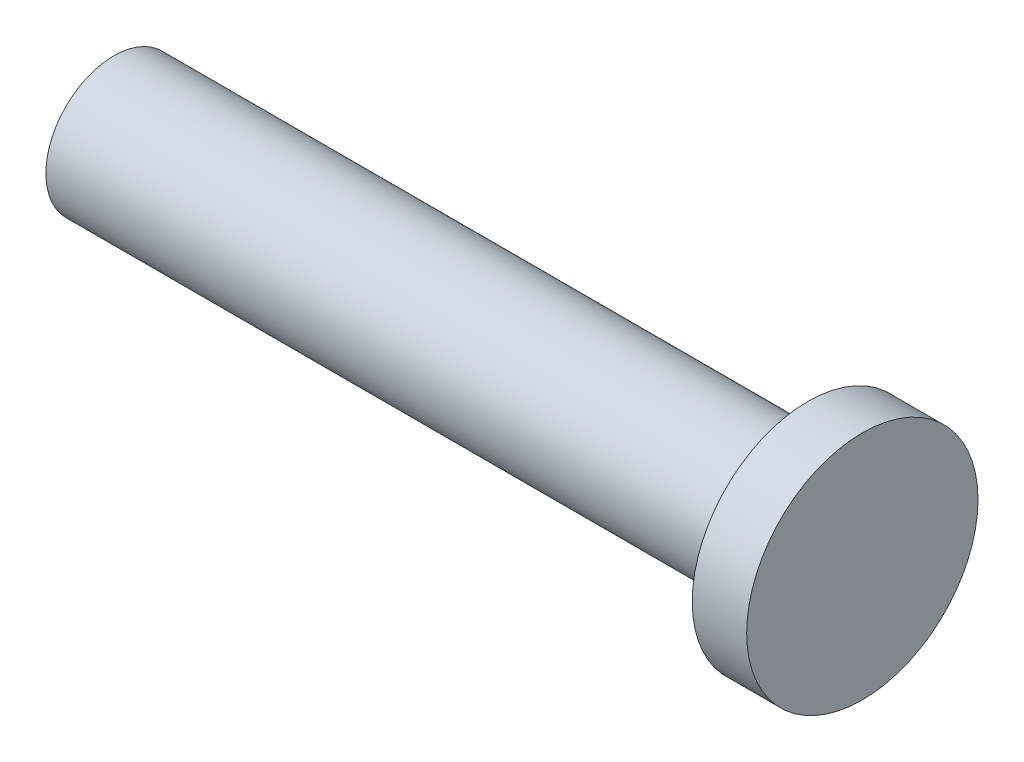
SolidWorks part; units mm, degrees
ref_plane "Front Plane" through (0, 0, 0) normal (0, 0, 1) x (1, 0, 0)
ref_plane "Top Plane" through (0, 0, 0) normal (0, 1, 0) x (1, 0, 0)
ref_plane "Right Plane" through (0, 0, 0) normal (1, 0, 0) x (0, 0, -1)
sketch "Sketch1" plane through (0, 0, 0) normal (1, 0, 0) x (0, 0, -1)
  circle A0 centre (0, 0) radius 2.5
  dimension "D1" = 5
extrude "Boss-Extrude1" add sketch "Sketch1" along normal blind 27.5
sketch "Sketch2" plane through (27.5, 0, 0) normal (1, 0, 0) x (0, 0, -1)
  circle A0 centre (0, 0) radius 4.25
  circle A1 centre (0, 0) radius 2.5
  circle A2 centre (0, 0) radius 2.5
  dimension "D1" = 0
  dimension "D2" = 1.75
extrude "Boss-Extrude2" add sketch "Sketch2" against normal blind 2
scale "Scale1" scale about centroid uniform scaling yes scale factor 1.5
